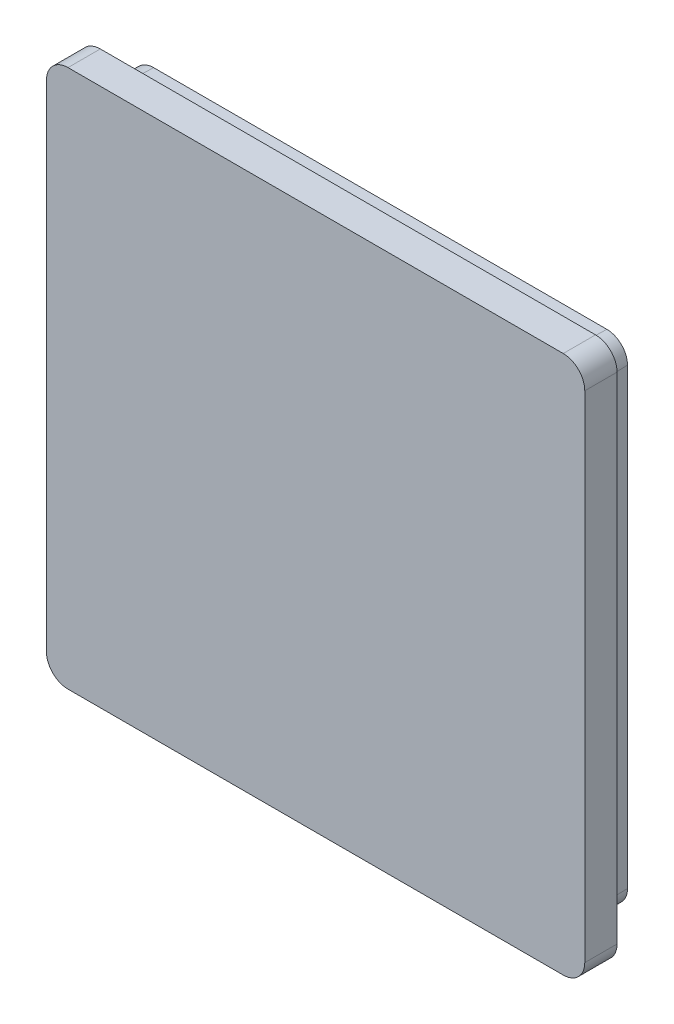
SolidWorks part; units mm, degrees
ref_plane "Front Plane" through (0, 0, 0) normal (1, 0, 0) x (0, 1, 0)
ref_plane "Top Plane" through (0, 0, 0) normal (0, 0, 1) x (0, 1, 0)
ref_plane "Right Plane" through (0, 0, 0) normal (0, 1, 0) x (-1, 0, 0)
sketch "Sketch1" plane through (0, 0, 0) normal (0, 0, 1) x (0, 1, 0)
  line L1 (-23, -25) -> (23, -25)
  line L2 (-25, -23) -> (-25, 23)
  line L3 (-23, 25) -> (23, 25)
  line L4 (25, -23) -> (25, 23)
  line L5 (-25, -25) -> (25, 25) construction
  line L6 (-25, 25) -> (25, -25) construction
  arc A0 (-23, -25) -> (-25, -23) centre (-23, -23) cw
  arc A1 (-25, 23) -> (-23, 25) centre (-23, 23) cw
  arc A2 (23, 25) -> (25, 23) centre (23, 23) cw
  arc A3 (23, -25) -> (25, -23) centre (23, -23) ccw
  point P0 (0, 0)
  dimension "D2" = 2
  dimension "D1" = 50
extrude "Boss-Extrude1" add sketch "Sketch1" along normal blind 3
sketch "Sketch2" plane through (0, 0, 0) normal (0, 0, -1) x (1, 0, 0)
  line L1 (-21.05, -23.05) -> (21.05, -23.05)
  line L2 (-23.05, -21.05) -> (-23.05, 21.05)
  line L3 (-21.05, 23.05) -> (21.05, 23.05)
  line L4 (23.05, -21.05) -> (23.05, 21.05)
  line L5 (-23.05, -23.05) -> (23.05, 23.05) construction
  line L6 (-23.05, 23.05) -> (23.05, -23.05) construction
  arc A0 (21.05, -23.05) -> (23.05, -21.05) centre (21.05, -21.05) ccw
  arc A1 (-21.05, -23.05) -> (-23.05, -21.05) centre (-21.05, -21.05) cw
  arc A2 (-23.05, 21.05) -> (-21.05, 23.05) centre (-21.05, 21.05) cw
  arc A3 (21.05, 23.05) -> (23.05, 21.05) centre (21.05, 21.05) cw
  point P0 (0, 0)
  dimension "D2" = 2
  dimension "D1" = 46.1
extrude "Boss-Extrude2" add sketch "Sketch2" along normal blind 3 draft 1.5
